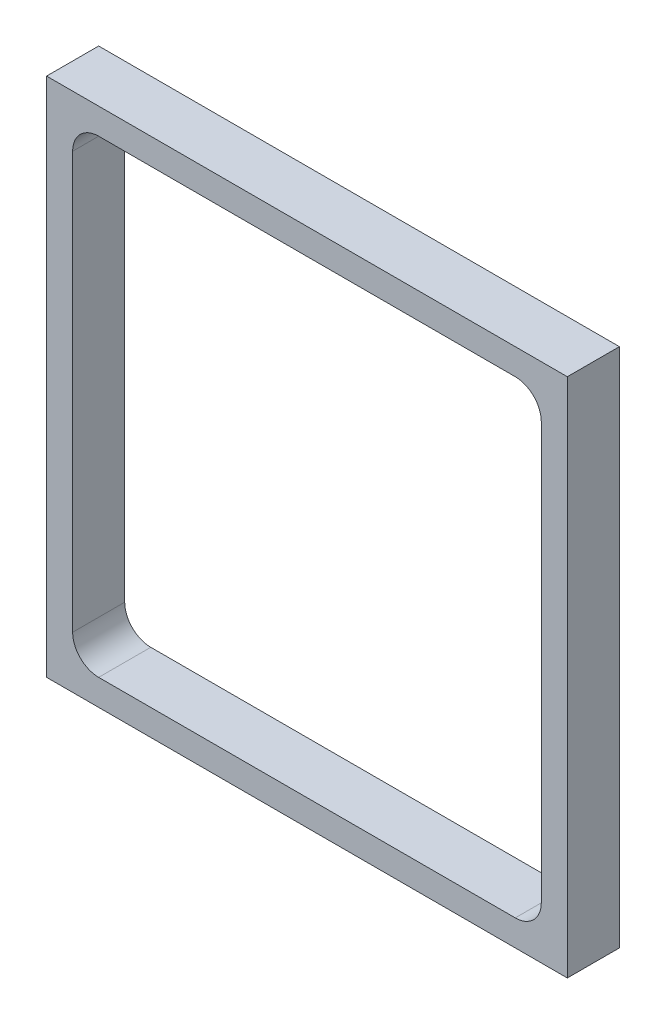
SolidWorks part; units mm, degrees
material "ABS"
ref_plane "Front Plane" through (0, 0, 0) normal (0, 0, 1) x (1, 0, 0)
ref_plane "Top Plane" through (0, 0, 0) normal (0, 1, 0) x (1, 0, 0)
ref_plane "Right Plane" through (0, 0, 0) normal (1, 0, 0) x (0, 0, -1)
sketch "Sketch1" plane through (0, 0, 0) normal (0, 0, 1) x (1, 0, 0)
  line L1 (-63.5, -63.5) -> (63.5, -63.5)
  line L2 (-63.5, -63.5) -> (-63.5, 63.5)
  line L3 (-63.5, 63.5) -> (63.5, 63.5)
  line L4 (63.5, -63.5) -> (63.5, 63.5)
  line L5 (-63.5, -63.5) -> (63.5, 63.5) construction
  line L6 (-63.5, 63.5) -> (63.5, -63.5) construction
  line L7 (-57.15, -57.15) -> (57.15, -57.15)
  line L8 (-57.15, -57.15) -> (-57.15, 57.15)
  line L9 (-57.15, 57.15) -> (57.15, 57.15)
  line L10 (57.15, -57.15) -> (57.15, 57.15)
  line L11 (-57.15, -57.15) -> (57.15, 57.15) construction
  line L12 (-57.15, 57.15) -> (57.15, -57.15) construction
  point P0 (0, 0)
  point P6 (0, 0)
  dimension "D1" = 127
  dimension "D2" = 127
  dimension "D3" = 6.35
extrude "Boss-Extrude1" add sketch "Sketch1" against normal blind 12.7
fillet "Fillet1" radius 6.35 4 edges at (57.15, -57.15, -6.35) (-57.15, -57.15, -6.35) (-57.15, 57.15, -6.35) (57.15, 57.15, -6.35)
ref_plane "Plane1" through (0, 63.5, 0) normal (0, 1, 0) x (1, 0, 0)
ref_plane "Plane2" through (0, 0, 0) normal (0, 1, 0) x (1, 0, 0)
